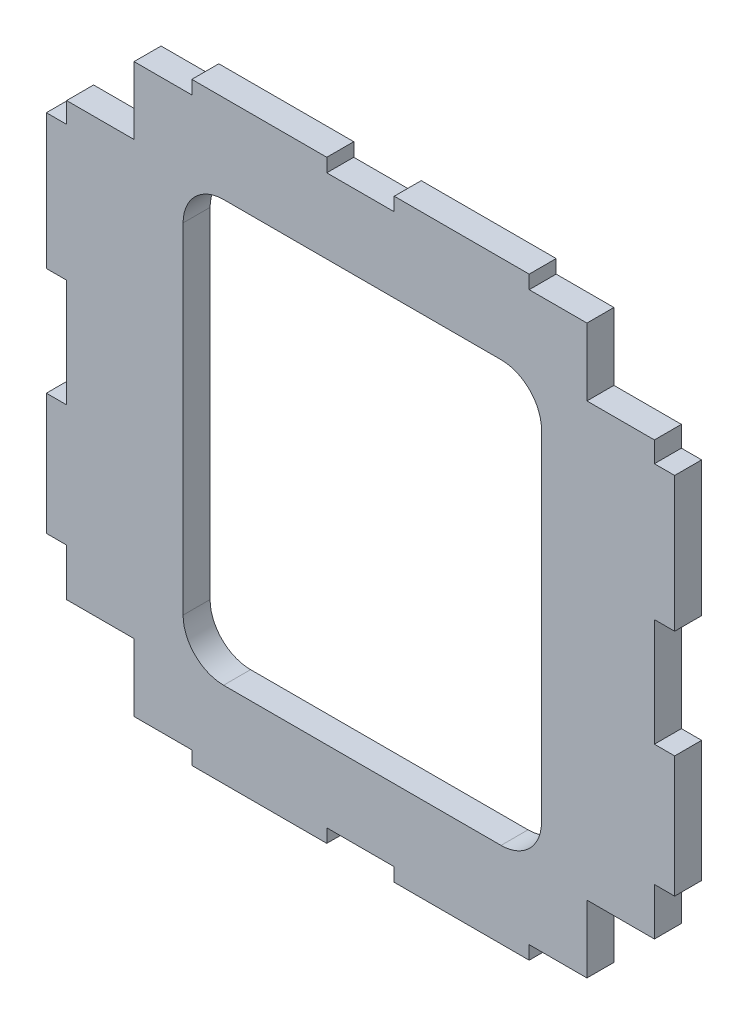
SolidWorks part; units mm, degrees
ref_plane "前视基准面" through (0, 0, 0) normal (0, 0, 1) x (1, 0, 0)
ref_plane "上视基准面" through (0, 0, 0) normal (0, 1, 0) x (1, 0, 0)
ref_plane "右视基准面" through (0, 0, 0) normal (1, 0, 0) x (0, 0, -1)
sketch "Model" plane through (0, 0, 0) normal (0, 0, 1) x (1, 0, 0)
  line L0 (55.5813, 45.478) -> (35.0213, 45.478)
  line L1 (58.5813, 42.478) -> (58.5813, 17.308)
  line L2 (35.0213, 14.308) -> (55.5813, 14.308)
  line L3 (32.0213, 42.478) -> (32.0213, 17.308)
  line L4 (28.3878, 51.0144) -> (32.6678, 51.0144)
  line L5 (32.6678, 51.0144) -> (32.6678, 52.0148)
  line L6 (32.6678, 52.0148) -> (42.6678, 52.0148)
  line L7 (42.6678, 52.0148) -> (42.6678, 51.0144)
  line L8 (42.6678, 51.0144) -> (47.6678, 51.0144)
  line L9 (47.6678, 51.0144) -> (47.6678, 52.0148)
  line L10 (47.6678, 52.0148) -> (57.6678, 52.0148)
  line L11 (57.6678, 52.0148) -> (57.6678, 51.0144)
  line L12 (57.6678, 51.0144) -> (61.9478, 51.0144)
  line L13 (28.3878, 8.9809) -> (32.6678, 8.9809)
  line L14 (32.6678, 8.9809) -> (32.6678, 7.9806)
  line L15 (32.6678, 7.9806) -> (42.6678, 7.9806)
  line L16 (42.6678, 7.9806) -> (42.6678, 8.9809)
  line L17 (42.6678, 8.9809) -> (47.6678, 8.9809)
  line L18 (47.6678, 8.9809) -> (47.6678, 7.9806)
  line L19 (47.6678, 7.9806) -> (57.6678, 7.9806)
  line L20 (57.6678, 7.9806) -> (57.6678, 8.9809)
  line L21 (57.6678, 8.9809) -> (61.9478, 8.9809)
  line L22 (21.8878, 34.4844) -> (21.8878, 44.4844)
  line L23 (23.3878, 46.0144) -> (28.3878, 46.0144)
  line L24 (28.3878, 46.0144) -> (28.3878, 51.0144)
  line L25 (23.3878, 13.9809) -> (28.3878, 13.9809)
  line L26 (28.3878, 13.9809) -> (28.3878, 8.9809)
  line L27 (23.3878, 46.0144) -> (23.3878, 44.4844)
  line L28 (23.3878, 44.4844) -> (21.8878, 44.4844)
  line L29 (21.8878, 34.4844) -> (23.3878, 34.4844)
  line L30 (23.3878, 34.4844) -> (23.3878, 26.4844)
  line L31 (23.3878, 26.4844) -> (21.8878, 26.4844)
  line L32 (21.8878, 17.4844) -> (23.3878, 17.4844)
  line L33 (23.3878, 17.4844) -> (23.3878, 13.9809)
  line L34 (68.4478, 34.4844) -> (68.4478, 44.4844)
  line L35 (66.9478, 46.0144) -> (61.9478, 46.0144)
  line L36 (61.9478, 46.0144) -> (61.9478, 51.0144)
  line L37 (66.9478, 13.9809) -> (61.9478, 13.9809)
  line L38 (61.9478, 13.9809) -> (61.9478, 8.9809)
  line L39 (66.9478, 46.0144) -> (66.9478, 44.4844)
  line L40 (66.9478, 44.4844) -> (68.4478, 44.4844)
  line L41 (68.4478, 34.4844) -> (66.9478, 34.4844)
  line L42 (66.9478, 34.4844) -> (66.9478, 26.4844)
  line L43 (66.9478, 26.4844) -> (68.4478, 26.4844)
  line L44 (68.4478, 26.4844) -> (68.4478, 17.4844)
  line L45 (68.4478, 17.4844) -> (66.9478, 17.4844)
  line L46 (66.9478, 17.4844) -> (66.9478, 13.9809)
  line L47 (21.8878, 26.4844) -> (21.8878, 17.4844)
  arc A0 (35.0213, 45.478) -> (32.0213, 42.478) centre (35.0213, 42.478) ccw
  arc A1 (58.5813, 42.478) -> (55.5813, 45.478) centre (55.5813, 42.478) ccw
  arc A2 (32.0213, 17.308) -> (35.0213, 14.308) centre (35.0213, 17.308) ccw
  arc A3 (55.5813, 14.308) -> (58.5813, 17.308) centre (55.5813, 17.308) ccw
extrude "凸台-拉伸1" add sketch "Model" along normal blind 2
